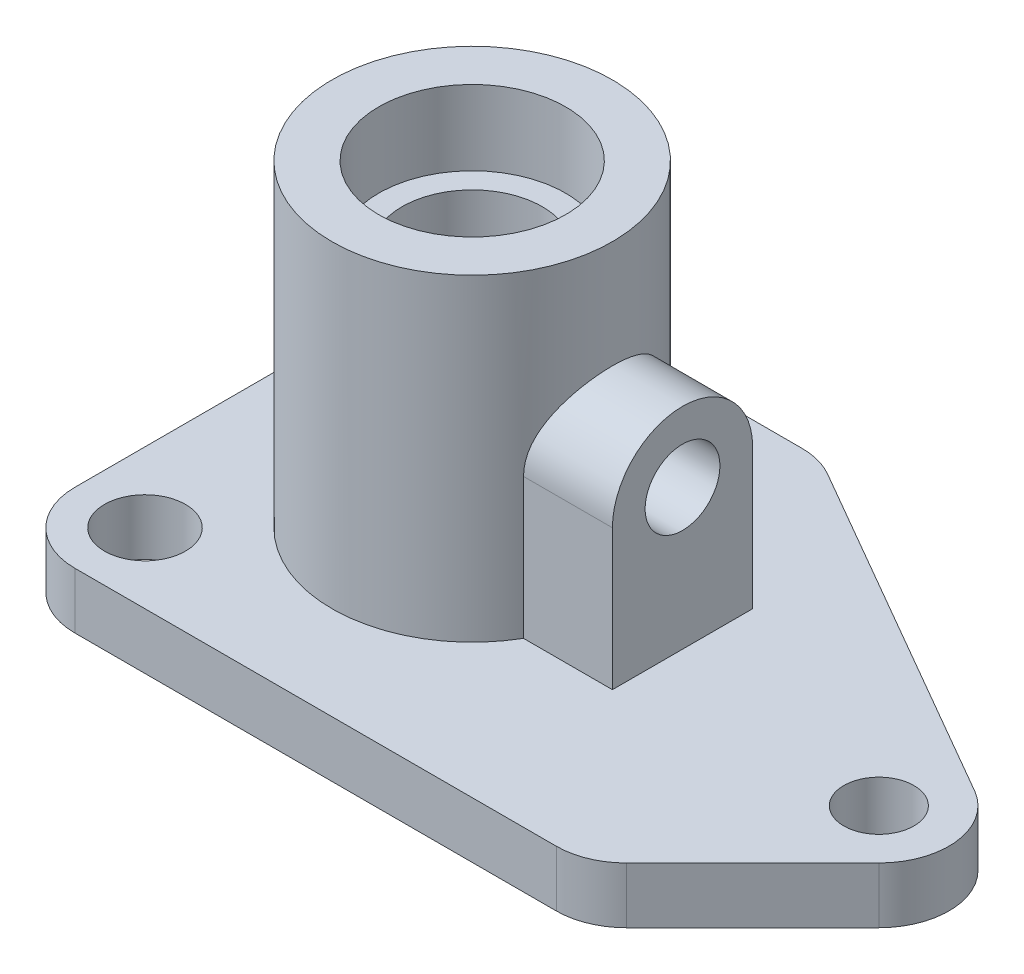
SolidWorks part; units mm, degrees
ref_plane "Front Plane" through (0, 0, 0) normal (0, 0, 1) x (1, 0, 0)
ref_plane "Top Plane" through (0, 0, 0) normal (0, 1, 0) x (1, 0, 0)
ref_plane "Right Plane" through (0, 0, 0) normal (1, 0, 0) x (0, 0, -1)
sketch "Sketch1" plane through (0, 0, 0) normal (0, 1, 0) x (1, 0, 0)
  line L0 (0, 15) -> (0, 85)
  line L5 (15, 100) -> (70.5218, 100)
  line L6 (78.0218, 97.9904) -> (152.5, 54.9904)
  line L7 (155.6066, 31.3934) -> (128.6066, 4.3934)
  line L8 (118, 0) -> (15, 0)
  arc A0 (152.5, 54.9904) -> (155.6066, 31.3934) centre (145, 42) cw
  arc A1 (15, 0) -> (0, 15) centre (15, 15) cw
  arc A2 (0, 85) -> (15, 100) centre (15, 85) cw
  circle A3 centre (15, 85) radius 7.5
  circle A4 centre (15, 15) radius 8.6671
  circle A5 centre (145, 42) radius 7.5
  arc A6 (78.0218, 97.9904) -> (70.5218, 100) centre (70.5218, 85) ccw
  arc A7 (128.6066, 4.3934) -> (118, 0) centre (118, 15) cw
  point P12 (0, 0)
  point P15 (0, 100)
  dimension "D4" = 15
  dimension "D5" = 15
  dimension "D6" = 17.3342
  dimension "D7" = 15
  dimension "D10" = 15
  dimension "D1" = 100
  dimension "D2" = 30
  dimension "D3" = 135
  dimension "D8" = 145
  dimension "D9" = 42
extrude "Boss-Extrude1" add sketch "Sketch1" along normal blind 12
sketch "Sketch2" plane through (0, 12, 0) normal (0, 1, 0) x (1, 0, 0)
  line L0 (0, 85) -> (0, 15) construction
  line L1 (70.5218, 100) -> (15, 100) construction
  circle A0 centre (50, 50) radius 30
  dimension "D3" = 60
  dimension "D1" = 50
  dimension "D2" = 50
extrude "Boss-Extrude2" add sketch "Sketch2" along normal blind 68
hole_wizard "Hole1" positions "Sketch3" profile "Sketch5" legacy end condition through all
sketch "Sketch3" plane through (0, 80, 0) normal (0, 1, 0) x (1, 0, 0)
  point P0 (50, 50)
sketch "Sketch5" plane through (50, 80, -50) normal (1, 0, 0) x (0, 0, 1)
  line L0 (0, 0) -> (0, 89.0129)
  line L1 (0, 89.0129) -> (15, 80)
  line L2 (15, 80) -> (15, 16)
  line L3 (15, 16) -> (20, 16)
  line L4 (20, 0) -> (0, 0)
  line L5 (0, -11.3109) -> (0, 121.1557) construction
  line L6 (0, 89.0129) -> (-15, 80) construction
  line L7 (20, 16) -> (20, 0)
  dimension "Depth" = 80
  dimension "Drill Angle" = 118
  dimension "Diameter" = 30
  dimension "C-Bore Diameter" = 40
  dimension "C-Bore Depth" = 16
ref_plane "Plane1" through (95, 0, 0) normal (1, 0, 0) x (0, 0, -1)
sketch "Sketch6" plane through (95, 0, 0) normal (1, 0, 0) x (0, 0, -1)
  line L0 (35, 42) -> (35, 12)
  line L1 (54.9904, 12) -> (31.3934, 12) construction
  line L2 (35, 12) -> (65, 12)
  line L3 (54.9904, 12) -> (97.9904, 12) construction
  line L4 (65, 12) -> (65, 42)
  line L5 (4.3934, 0) -> (31.3934, 0) construction
  line L6 (50, 80) -> (50, 12) construction
  arc A0 (65, 42) -> (35, 42) centre (50, 42) ccw
  point P13 (0, 0)
  point P16 (0, 0)
  point P17 (0, 0)
  point P18 (0, 0)
  dimension "D1" = 42
  dimension "D2" = 65
extrude "Boss-Extrude3" add sketch "Sketch6" against normal up to surface (19.0192 mm away)
sketch "Sketch7" plane through (95, 0, 0) normal (1, 0, 0) x (0, 0, -1)
  circle A0 centre (50, 42) radius 8
  dimension "D1" = 16
extrude "Cut-Extrude1" cut sketch "Sketch7" against normal up to surface (32.3114 mm away)
